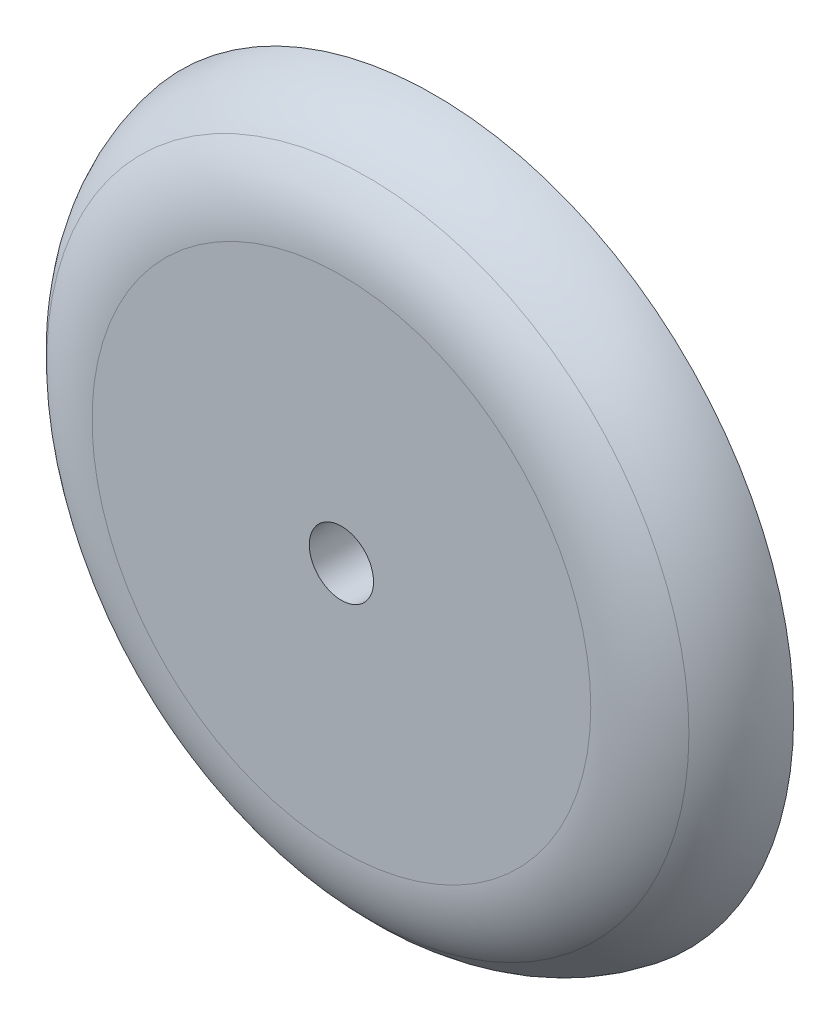
SolidWorks part; units mm, degrees
material "Plain Carbon Steel"
ref_plane "Front Plane" through (0, 0, 0) normal (0, 0, 1) x (1, 0, 0)
ref_plane "Top Plane" through (0, 0, 0) normal (0, 1, 0) x (1, 0, 0)
ref_plane "Right Plane" through (0, 0, 0) normal (1, 0, 0) x (0, 0, -1)
sketch "Sketch1" plane through (0, 0, 0) normal (1, 0, 0) x (0, 0, -1)
  line L0 (-15.3879, 0) -> (0, 0) construction
  line L1 (0, 0) -> (0, 8.5) construction
  line L2 (0, 8.5) -> (-24.7, 8.5)
  line L3 (-24.7, 66) -> (-24.7, 8.5)
  line L4 (0, 8.5) -> (0, 95)
  line L5 (-3.1453, 80.2681) -> (-3.1453, 26.5772)
  line L6 (-3.1453, 80.2681) -> (-15.1453, 80.2681)
  line L7 (-3.1453, 26.5772) -> (-15.1453, 26.5772)
  line L8 (-15.1453, 80.2681) -> (-15.1453, 26.5772)
  line L9 (-3.1453, 80.2681) -> (-15.1453, 26.5772) construction
  line L10 (-3.1453, 26.5772) -> (-15.1453, 80.2681) construction
  arc A0 (0, 95) -> (-17.7326, 85) centre (4.6479, 66.0357) ccw
  arc A1 (-17.7326, 85) -> (-24.7, 66) centre (4.6901, 66) ccw
  point P11 (-9.1453, 53.4226)
  point P12 (0, 95)
  point P18 (0, 60.8769)
  dimension "D1" = 66
  dimension "D2" = 19
  dimension "D3" = 95
  dimension "D4" = 24.7
  dimension "D5" = 12
  dimension "D7" = 17
revolve "Revolve1" add sketch "Sketch1" angle 360 about L0
